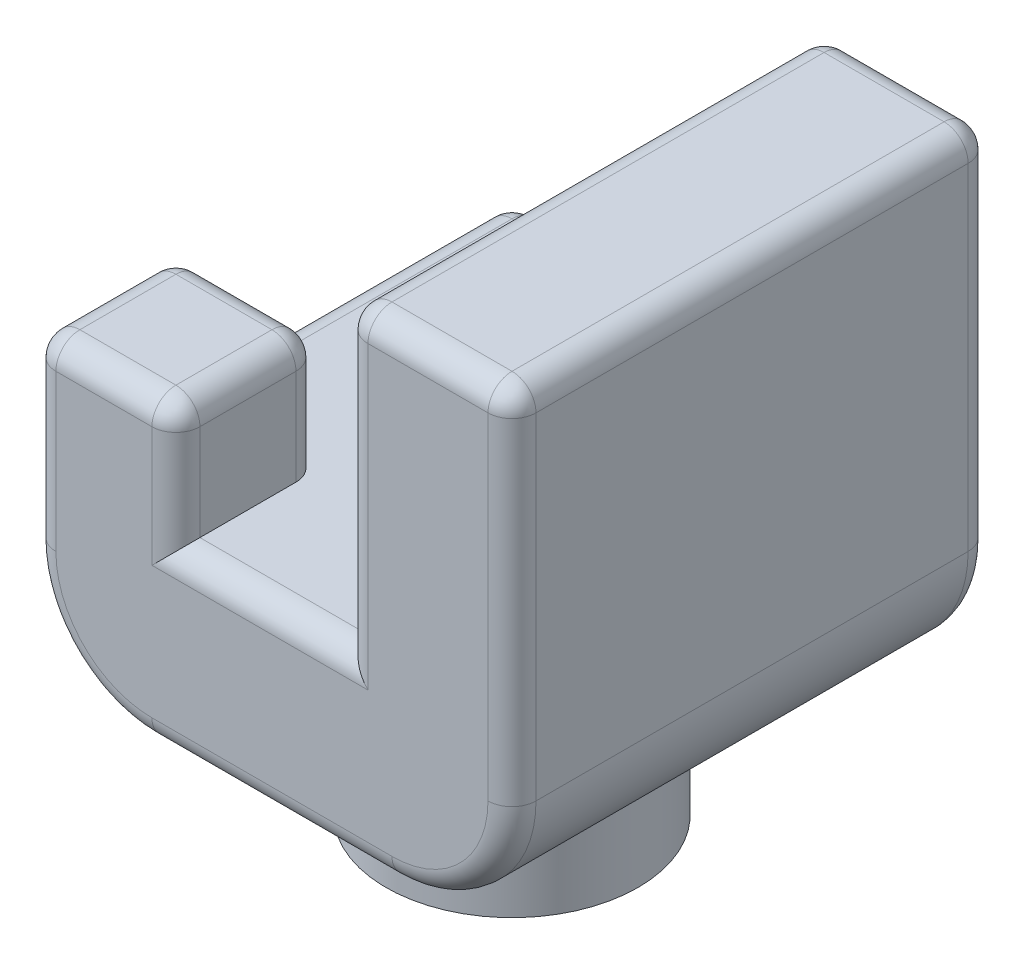
SolidWorks part; units mm, degrees
ref_plane "Front Plane" through (0, 0, 0) normal (0, 0, 1) x (1, 0, 0)
ref_plane "Top Plane" through (0, 0, 0) normal (0, 1, 0) x (1, 0, 0)
ref_plane "Right Plane" through (0, 0, 0) normal (1, 0, 0) x (0, 0, -1)
sketch "Sketch1" plane through (0, 0, 0) normal (0, 0, 1) x (1, 0, 0)
  line L1 (-10, 10) -> (10, 10)
  line L2 (-10, 10) -> (-10, -10)
  line L3 (-10, -10) -> (10, -10)
  line L4 (10, 10) -> (10, -10)
  line L5 (-10, 10) -> (10, -10) construction
  line L6 (-10, -10) -> (10, 10) construction
  point P0 (0, 0)
extrude "Boss-Extrude1" add sketch "Sketch1" along normal blind 20
sketch "Sketch2" plane through (0, 0, 20) normal (0, 0, 1) x (1, 0, 0)
  line L1 (-10, 10) -> (-10, -10) construction
  line L5 (3, -2.5) -> (3, 10)
  line L6 (10, 10) -> (-10, 10) construction
  line L10 (-10, 2.5) -> (-10, 10)
  line L11 (-10, 10) -> (3, 10)
  line L12 (-10, 2.5) -> (-4, 2.5)
  line L13 (-4, 2.5) -> (-4, -2.5)
  line L14 (-4, -2.5) -> (3, -2.5)
extrude "Cut-Extrude1" cut sketch "Sketch2" against normal blind 25
sketch "Sketch3" plane through (-10, 0, 0) normal (-1, 0, 0) x (0, 0, 1)
  line L0 (0, 2.5) -> (0, -2.5)
  line L1 (0, 2.5) -> (0, -10) construction
  line L2 (0, -2.5) -> (14, -2.5)
  line L3 (14, -2.5) -> (14, 2.5)
  line L4 (14, 2.5) -> (0, 2.5)
extrude "Cut-Extrude2" cut sketch "Sketch3" against normal blind 12
fillet "Fillet2" radius 5 2 edges at (-10, -10, 10) (10, -10, 10)
fillet "Fillet3" radius 1 15 edges at (-10, -1.25, 20) (-8.5355, -8.5355, 20) (0, -10, 20) (8.5355, -8.5355, 20) (10, 2.5, 20) (-10, -3.75, 0) (-8.5355, -8.5355, 0) (0, -10, 0) (8.5355, -8.5355, 0) (-10, 0, 14) (-4, 0, 14) (3, 3.75, 0) (-4, 0, 20) (3, 3.75, 20) (10, 2.5, 0)
fillet "Fillet4" radius 1 20 edges at (-2.5, -2.5, 0) (-9.7071, -2.5, 0.2929) (3.2929, 10, 0.2929) (6.5, 10, 0) (9.7071, 10, 0.2929) (10, 10, 10) (9.7071, 10, 19.7071) (6.5, 10, 20) (3.2929, 10, 19.7071) (-9.7071, 2.5, 14.2929) (-4.2929, 2.5, 14.2929) (-4, 2.5, 17) (-4.2929, 2.5, 19.7071) (-7, 2.5, 20) (-9.7071, 2.5, 19.7071) (-10, -2.5, 8) (-0.5, -2.5, 20) (3, 10, 10) (-7, 2.5, 14) (-10, 2.5, 17)
sketch "Sketch4" plane through (0, -10, 0) normal (0, -1, 0) x (1, 0, 0)
  circle A0 centre (0, 10) radius 5.25
extrude "Boss-Extrude2" add sketch "Sketch4" along normal blind 5
